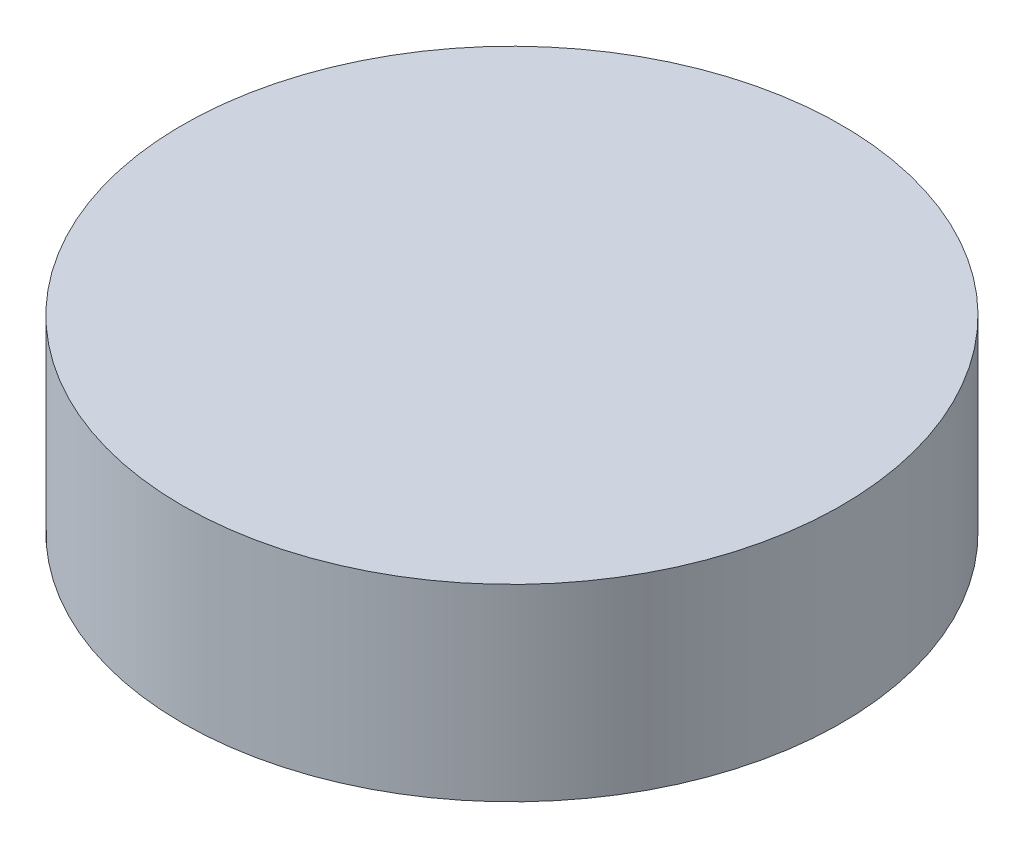
SolidWorks part; units mm, degrees
ref_plane "Front Plane" through (0, 0, 0) normal (0, 0, 1) x (1, 0, 0)
ref_plane "Top Plane" through (0, 0, 0) normal (0, 1, 0) x (1, 0, 0)
ref_plane "Right Plane" through (0, 0, 0) normal (1, 0, 0) x (0, 0, -1)
sketch "Sketch1" plane through (0, 0, 0) normal (0, 1, 0) x (1, 0, 0)
  circle A0 centre (0, 0) radius 35
  dimension "D1" = 70
extrude "Boss-Extrude1" add sketch "Sketch1" along normal blind 20
